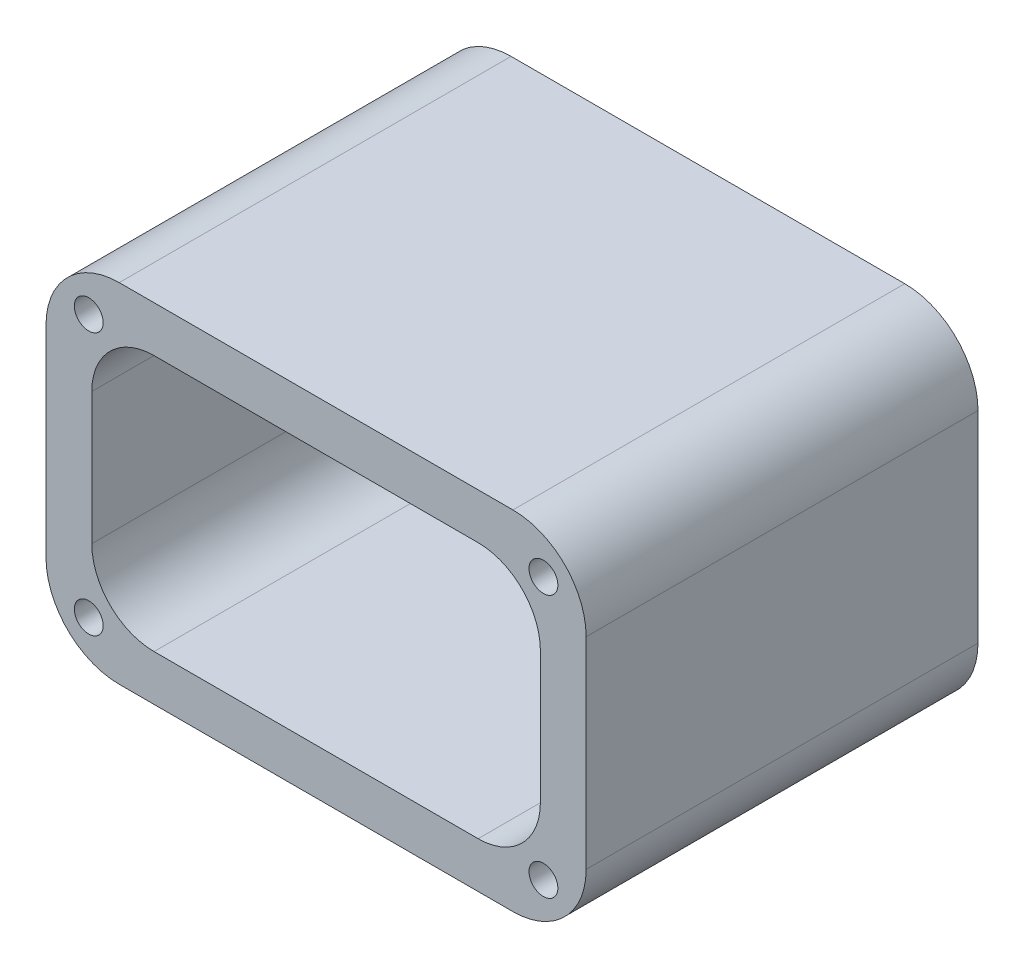
SolidWorks part; units mm, degrees
ref_plane "Front Plane" through (0, 0, 0) normal (0, 0, 1) x (1, 0, 0)
ref_plane "Top Plane" through (0, 0, 0) normal (0, 1, 0) x (1, 0, 0)
ref_plane "Right Plane" through (0, 0, 0) normal (1, 0, 0) x (0, 0, -1)
sketch "Sketch2" plane through (0, 0, 0) normal (0, 0, 1) x (1, 0, 0)
  line L1 (0, 0) -> (37.465, 0)
  line L2 (0, 0) -> (0, 24.13)
  line L3 (0, 24.13) -> (37.465, 24.13)
  line L4 (37.465, 0) -> (37.465, 24.13)
  dimension "D1" = 24.13
  dimension "D2" = 37.465
extrude "Boss-Extrude1" add sketch "Sketch2" along normal blind 24.892
sketch "Sketch3" plane through (0, 0, 24.892) normal (0, 0, 1) x (1, 0, 0)
  line L0 (37.465, 12.065) -> (34.29, 12.065)
  line L1 (37.465, 0) -> (37.465, 24.13) construction
  line L2 (18.7325, 24.13) -> (18.7325, 20.955)
  line L3 (37.465, 24.13) -> (0, 24.13) construction
  line L4 (0, 12.065) -> (3.175, 12.065)
  line L5 (0, 24.13) -> (0, 0) construction
  line L6 (18.7325, 0) -> (18.7325, 3.175)
  line L7 (0, 0) -> (37.465, 0) construction
  line L8 (3.175, 7.493) -> (3.175, 16.637)
  line L9 (7.493, 20.955) -> (29.972, 20.955)
  line L10 (34.29, 16.637) -> (34.29, 7.493)
  line L11 (29.972, 3.175) -> (7.493, 3.175)
  arc A0 (29.972, 20.955) -> (34.29, 16.637) centre (29.972, 16.637) cw
  arc A1 (34.29, 7.493) -> (29.972, 3.175) centre (29.972, 7.493) cw
  arc A2 (7.493, 3.175) -> (3.175, 7.493) centre (7.493, 7.493) cw
  arc A3 (3.175, 16.637) -> (7.493, 20.955) centre (7.493, 16.637) cw
  point P19 (3.175, 12.065)
  dimension "D5" = 4.318
  dimension "D1" = 3.175
  dimension "D2" = 3.175
  dimension "D3" = 3.175
  dimension "D4" = 3.175
extrude "Cut-Extrude1" cut sketch "Sketch3" against normal offset from surface (20.701 mm away) 4.191 contours A3 L8 A2 L11 A1 L10 A0 L9 up to face at (18.7325, 12.065, 0)
sketch "Sketch4" plane through (0, 0, 4.191) normal (0, 0, 1) x (1, 0, 0)
  line L5 (29.972, 3.175) -> (7.493, 3.175) construction
  line L7 (29.972, 3.175) -> (7.493, 3.175)
  line L8 (3.175, 16.637) -> (3.175, 7.493)
  line L9 (7.493, 3.175) -> (29.972, 3.175)
  line L10 (34.29, 7.493) -> (34.29, 16.637)
  line L11 (29.972, 20.955) -> (7.493, 20.955)
  line L12 (3.175, 16.637) -> (3.175, 7.493)
  line L13 (7.493, 3.175) -> (22.878, 3.175)
  line L15 (29.972, 20.955) -> (7.493, 20.955)
  line L16 (32.087, 8.5701) -> (32.0708, 10.8825)
  line L17 (27.4297, 15.4623) -> (21.5877, 15.4458)
  line L18 (16.931, 10.882) -> (16.9471, 8.5707)
  line L19 (21.5877, 3.9904) -> (27.4297, 4.0068)
  line L26 (19.0477, 16.2033) -> (29.9697, 16.2033)
  line L27 (34.1607, 12.0123) -> (34.1607, 7.4403)
  line L28 (19.0477, 3.2493) -> (29.9697, 3.2493)
  line L29 (14.8567, 12.0123) -> (14.8567, 7.4403)
  line L30 (24.5087, 16.2033) -> (24.5087, 3.2493) construction
  line L31 (14.8567, 9.7263) -> (34.1607, 9.7263) construction
  line L32 (16.9391, 9.7263) -> (32.0789, 9.7263) construction
  line L33 (24.5087, 15.4541) -> (24.5087, 3.9986) construction
  arc A4 (3.175, 7.493) -> (7.493, 3.175) centre (7.493, 7.493) ccw
  arc A5 (29.972, 3.175) -> (34.29, 7.493) centre (29.972, 7.493) ccw
  arc A6 (34.29, 16.637) -> (29.972, 20.955) centre (29.972, 16.637) ccw
  arc A7 (7.493, 20.955) -> (3.175, 16.637) centre (7.493, 16.637) ccw
  arc A8 (3.175, 7.493) -> (7.493, 3.175) centre (7.493, 7.493) ccw
  arc A10 (34.29, 16.637) -> (29.972, 20.955) centre (29.972, 16.637) ccw
  arc A11 (7.493, 20.955) -> (3.175, 16.637) centre (7.493, 16.637) ccw
  arc A14 (29.9697, 16.2033) -> (34.1607, 12.0123) centre (29.9697, 12.0123) cw
  arc A15 (29.9697, 3.2493) -> (34.1607, 7.4403) centre (29.9697, 7.4403) ccw
  arc A16 (14.8567, 7.4403) -> (19.0477, 3.2493) centre (19.0477, 7.4403) ccw
  arc A17 (19.0477, 16.2033) -> (14.8567, 12.0123) centre (19.0477, 12.0123) ccw
  spline S0 degree 2 poles (32.0708, 10.8825) (32.0732, 11.0351) (32.0535, 11.3845) (31.9835, 11.899) (31.6903, 12.8915) (30.7816, 14.2408) (29.419, 15.1192) (28.4147, 15.3932) (27.9094, 15.4522) (27.5548, 15.4648) (27.4297, 15.4623) knots 0 0 0 0.046875 0.09375 0.1875 0.375 0.625 0.8125 0.90625 0.953125 1 1 1
  spline S1 degree 2 poles (21.5877, 15.4458) (21.4628, 15.4487) (21.1067, 15.4373) (20.5958, 15.379) (19.5917, 15.1071) (18.2257, 14.2298) (17.3162, 12.886) (17.02, 11.8893) (16.9499, 11.3822) (16.9291, 11.0348) (16.931, 10.882) knots 0 0 0 0.046875 0.09375 0.1875 0.375 0.625 0.8125 0.90625 0.953125 1 1 1
  spline S2 degree 2 poles (16.9471, 8.5707) (16.9447, 8.4181) (16.9644, 8.0687) (17.0343, 7.5542) (17.3274, 6.5617) (18.2359, 5.2123) (19.5984, 4.3337) (20.6027, 4.0596) (21.108, 4.0005) (21.4626, 3.9879) (21.5877, 3.9904) knots 0 0 0 0.046875 0.09375 0.1875 0.375 0.625 0.8125 0.90625 0.953125 1 1 1
  spline S3 degree 2 poles (27.4297, 4.0068) (27.5546, 4.0039) (27.9107, 4.0153) (28.4216, 4.0736) (29.4258, 4.3454) (30.7919, 5.2225) (31.7015, 6.5662) (31.9978, 7.5629) (32.068, 8.07) (32.0888, 8.4173) (32.087, 8.5701) knots 0 0 0 0.046875 0.09375 0.1875 0.375 0.625 0.8125 0.90625 0.953125 1 1 1
  dimension "D2" = 10.922
  dimension "D3" = 5.842
  dimension "D4" = 4.572
  dimension "D5" = 10.922
  dimension "D6" = 2.3114
  dimension "D7" = 5.842
  dimension "D8" = 15.1395
  dimension "D9" = 19.304
  dimension "D10" = 12.954
  dimension "D11" = 11.4554
  dimension "D1" = 0
extrude "Cut-Extrude3" cut sketch "Sketch4" against normal blind 4.191
sketch "Sketch5" plane through (0, 0, 4.191) normal (0, 0, 1) x (1, 0, 0)
  line L0 (24.5087, 15.4541) -> (15.3229, 15.4541) construction
  line L1 (27.4297, 15.4623) -> (21.5877, 15.4458) construction
  line L2 (3.175, 7.493) -> (3.175, 16.637) construction
  line L3 (7.0679, 19.3698) -> (7.0679, 3.7996)
  line L13 (7.0679, 15.4541) -> (3.175, 15.4541) construction
  line L14 (15.3229, 3.7996) -> (7.0679, 3.7996)
  line L15 (7.0679, 19.3698) -> (15.3229, 19.3698)
  line L16 (15.3229, 19.3698) -> (15.3229, 3.7996)
  line L17 (11.1954, 19.3698) -> (11.1954, 3.7996) construction
  circle A0 centre (11.1954, 11.5847) radius 1.27
  point P9 (11.1954, 8.8218)
  dimension "D2" = 2.54
  dimension "D1" = 8.255
  dimension "D3" = 15.5702
fillet "Fillet1" radius 5.08 4 edges at (37.465, 24.13, 12.446) (37.465, 0, 12.446) (0, 0, 12.446) (0, 24.13, 12.446)
sketch "Sketch7" plane through (0, 0, 24.892) normal (0, 0, 1) x (1, 0, 0)
  line L0 (7.493, 20.955) -> (29.972, 20.955) construction
  line L1 (34.29, 16.637) -> (34.29, 7.493) construction
  line L2 (29.972, 3.175) -> (7.493, 3.175) construction
  line L3 (3.175, 7.493) -> (3.175, 16.637) construction
  line L4 (7.493, 20.955) -> (29.972, 20.955)
  line L5 (34.29, 16.637) -> (34.29, 7.493)
  line L6 (29.972, 3.175) -> (7.493, 3.175)
  line L7 (3.175, 7.493) -> (3.175, 16.637)
  line L8 (18.7325, 24.13) -> (18.7325, 0) construction
  line L9 (0, 12.065) -> (37.465, 12.065) construction
  line L12 (37.465, 5.08) -> (37.465, 19.05)
  line L13 (32.385, 24.13) -> (5.08, 24.13)
  line L14 (0, 19.05) -> (0, 5.08)
  line L15 (5.08, 0) -> (32.385, 0)
  line L16 (37.465, 5.08) -> (37.465, 19.05)
  line L17 (32.385, 24.13) -> (5.08, 24.13)
  line L18 (0, 19.05) -> (0, 5.08)
  line L19 (5.08, 0) -> (32.385, 0)
  line L22 (6.4452, 1.2065) -> (31.0197, 1.2065)
  line L23 (35.5917, 5.7785) -> (35.5917, 18.3515)
  line L24 (31.0197, 22.9235) -> (6.4453, 22.9235)
  line L25 (1.8732, 18.3515) -> (1.8732, 5.7785)
  arc A0 (34.29, 16.637) -> (29.972, 20.955) centre (29.972, 16.637) ccw construction
  arc A1 (29.972, 3.175) -> (34.29, 7.493) centre (29.972, 7.493) ccw construction
  arc A2 (3.175, 7.493) -> (7.493, 3.175) centre (7.493, 7.493) ccw construction
  arc A3 (7.493, 20.955) -> (3.175, 16.637) centre (7.493, 16.637) ccw construction
  arc A4 (34.29, 16.637) -> (29.972, 20.955) centre (29.972, 16.637) ccw
  arc A5 (29.972, 3.175) -> (34.29, 7.493) centre (29.972, 7.493) ccw
  arc A6 (3.175, 7.493) -> (7.493, 3.175) centre (7.493, 7.493) ccw
  arc A7 (7.493, 20.955) -> (3.175, 16.637) centre (7.493, 16.637) ccw
  arc A12 (37.465, 19.05) -> (32.385, 24.13) centre (32.385, 19.05) ccw
  arc A13 (5.08, 24.13) -> (0, 19.05) centre (5.08, 19.05) ccw
  arc A14 (0, 5.08) -> (5.08, 0) centre (5.08, 5.08) ccw
  arc A15 (32.385, 0) -> (37.465, 5.08) centre (32.385, 5.08) ccw
  arc A16 (37.465, 19.05) -> (32.385, 24.13) centre (32.385, 19.05) ccw
  arc A17 (5.08, 24.13) -> (0, 19.05) centre (5.08, 19.05) ccw
  arc A18 (0, 5.08) -> (5.08, 0) centre (5.08, 5.08) ccw
  arc A19 (32.385, 0) -> (37.465, 5.08) centre (32.385, 5.08) ccw
  arc A20 (6.4453, 22.9235) -> (1.8732, 18.3515) centre (6.4453, 18.3515) ccw
  arc A21 (1.8732, 5.7785) -> (6.4452, 1.2065) centre (6.4453, 5.7785) ccw
  arc A22 (35.5917, 18.3515) -> (31.0197, 22.9235) centre (31.0197, 18.3515) ccw
  arc A23 (31.0197, 1.2065) -> (35.5917, 5.7785) centre (31.0197, 5.7785) ccw
  dimension "D1" = 0
extrude "Boss-Extrude3" add sketch "Sketch7" along normal blind 2.286 contours L22 A23 L23 A22 L24 A20 L25 A21 L13 L0 L1 L2 L3 L8 L9 L12
sketch "Sketch8" plane through (0, 0, 0) normal (-1, 0, 0) x (0, 0, 1)
  line L0 (0, 12.065) -> (24.892, 12.065) construction
  line L1 (0, 19.05) -> (0, 5.08) construction
  line L2 (24.892, 18.3515) -> (24.892, 5.7785) construction
  circle A0 centre (12.446, 12.065) radius 1.905
  dimension "D1" = 3.81
extrude "Cut-Extrude4" cut sketch "Sketch8" against normal blind 7.62
sketch "Sketch9" plane through (0, 0, 24.892) normal (0, 0, 1) x (1, 0, 0)
  line L4 (37.465, 5.08) -> (37.465, 19.05)
  line L5 (32.385, 24.13) -> (5.08, 24.13)
  line L6 (0, 19.05) -> (0, 5.08)
  line L7 (5.08, 0) -> (32.385, 0)
  line L8 (37.465, 5.08) -> (37.465, 19.05)
  line L9 (32.385, 24.13) -> (5.08, 24.13)
  line L10 (0, 19.05) -> (0, 5.08)
  line L11 (5.08, 0) -> (32.385, 0)
  line L12 (6.4452, 1.2065) -> (31.0197, 1.2065)
  line L13 (35.5917, 5.7785) -> (35.5917, 18.3515)
  line L14 (31.0197, 22.9235) -> (6.4453, 22.9235)
  line L15 (1.8732, 18.3515) -> (1.8732, 5.7785)
  line L16 (6.4452, 1.2065) -> (31.0197, 1.2065)
  line L17 (35.5917, 5.7785) -> (35.5917, 18.3515)
  line L18 (31.0197, 22.9235) -> (6.4453, 22.9235)
  line L19 (1.8732, 18.3515) -> (1.8732, 5.7785)
  arc A4 (37.465, 19.05) -> (32.385, 24.13) centre (32.385, 19.05) ccw
  arc A5 (5.08, 24.13) -> (0, 19.05) centre (5.08, 19.05) ccw
  arc A6 (0, 5.08) -> (5.08, 0) centre (5.08, 5.08) ccw
  arc A7 (32.385, 0) -> (37.465, 5.08) centre (32.385, 5.08) ccw
  arc A8 (37.465, 19.05) -> (32.385, 24.13) centre (32.385, 19.05) ccw
  arc A9 (5.08, 24.13) -> (0, 19.05) centre (5.08, 19.05) ccw
  arc A10 (0, 5.08) -> (5.08, 0) centre (5.08, 5.08) ccw
  arc A11 (32.385, 0) -> (37.465, 5.08) centre (32.385, 5.08) ccw
  arc A12 (31.0197, 1.2065) -> (35.5917, 5.7785) centre (31.0197, 5.7785) ccw
  arc A13 (35.5917, 18.3515) -> (31.0197, 22.9235) centre (31.0197, 18.3515) ccw
  arc A14 (6.4453, 22.9235) -> (1.8732, 18.3515) centre (6.4453, 18.3515) ccw
  arc A15 (1.8732, 5.7785) -> (6.4452, 1.2065) centre (6.4453, 5.7785) ccw
  arc A16 (31.0197, 1.2065) -> (35.5917, 5.7785) centre (31.0197, 5.7785) ccw
  arc A17 (35.5917, 18.3515) -> (31.0197, 22.9235) centre (31.0197, 18.3515) ccw
  arc A18 (6.4453, 22.9235) -> (1.8732, 18.3515) centre (6.4453, 18.3515) ccw
  arc A19 (1.8732, 5.7785) -> (6.4452, 1.2065) centre (6.4453, 5.7785) ccw
  dimension "D1" = 0
  dimension "D2" = 0
extrude "Boss-Extrude5" add sketch "Sketch9" along normal up to surface (2.286 mm away) up to face at (18.7325, 12.065, 27.178)
sketch "Sketch10" plane through (0, 0, 27.178) normal (0, 0, 1) x (1, 0, 0)
  line L0 (1.4879, 22.6421) -> (4.4397, 19.6903)
  line L3 (0, 12.065) -> (37.465, 12.065) construction
  line L4 (0, 19.05) -> (0, 5.08) construction
  line L5 (37.465, 5.08) -> (37.465, 19.05) construction
  line L6 (18.7325, 24.13) -> (18.7325, 0) construction
  line L7 (32.385, 24.13) -> (5.08, 24.13) construction
  line L8 (5.08, 0) -> (32.385, 0) construction
  arc A0 (5.08, 24.13) -> (0, 19.05) centre (5.08, 19.05) ccw construction
  arc A1 (7.493, 20.955) -> (3.175, 16.637) centre (7.493, 16.637) ccw construction
  circle A2 centre (2.9638, 21.1662) radius 1
  circle A3 centre (34.5012, 21.1662) radius 1
  circle A4 centre (34.5012, 2.9638) radius 1
  circle A5 centre (2.9638, 2.9638) radius 1
  dimension "D1" = 2
extrude "Cut-Extrude5" cut sketch "Sketch10" against normal blind 4 contours L0 A2 | L0 A2 | A3 | A4 | A5
